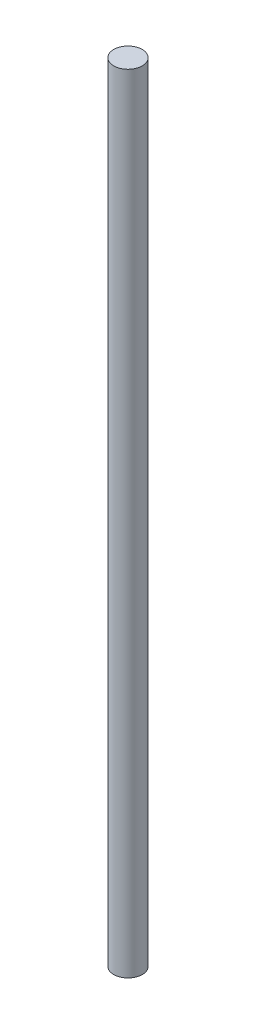
SolidWorks part; units mm, degrees
material "ABS"
ref_plane "Front Plane" through (0, 0, 0) normal (0, 0, 1) x (1, 0, 0)
ref_plane "Top Plane" through (0, 0, 0) normal (0, 1, 0) x (1, 0, 0)
ref_plane "Right Plane" through (0, 0, 0) normal (1, 0, 0) x (0, 0, -1)
sketch "Sketch1" plane through (0, 0, 0) normal (0, 1, 0) x (1, 0, 0)
  circle A0 centre (0, 0) radius 1.5875
  dimension "D1" = 3.175
extrude "Boss-Extrude1" add sketch "Sketch1" along normal blind 87.63
